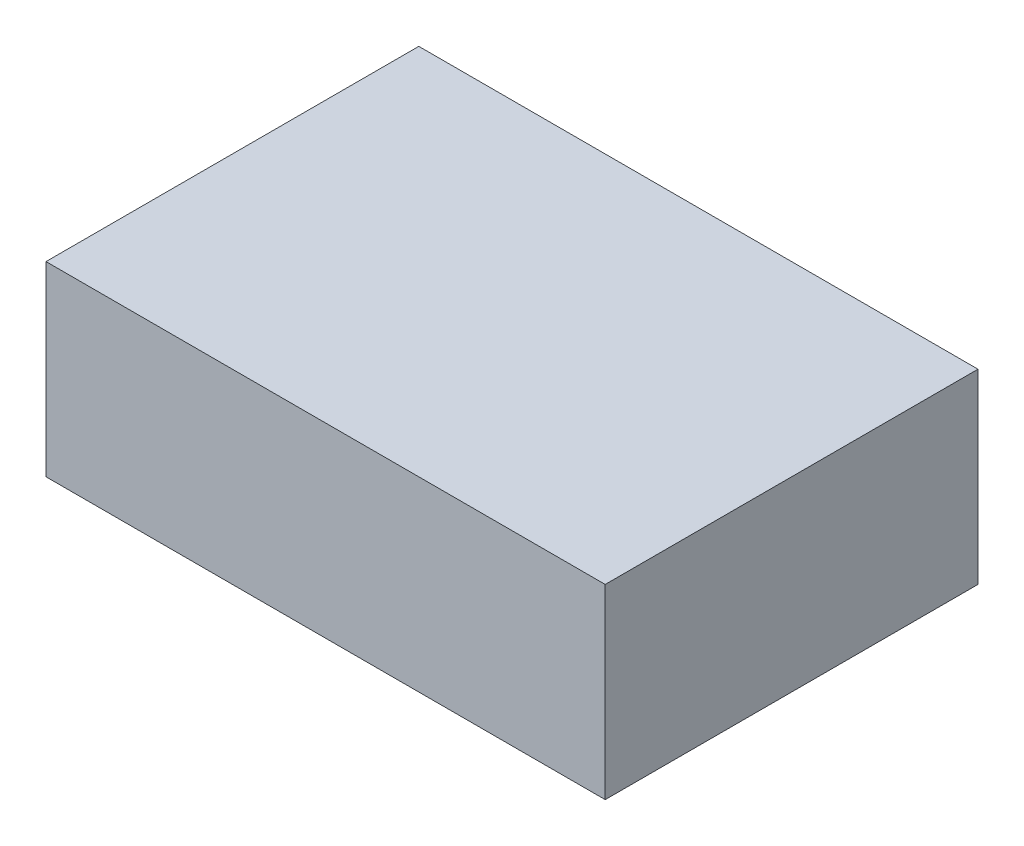
SolidWorks part; units mm, degrees
ref_plane "Front Plane" through (0, 0, 0) normal (0, 0, 1) x (1, 0, 0)
ref_plane "Top Plane" through (0, 0, 0) normal (0, 1, 0) x (1, 0, 0)
ref_plane "Right Plane" through (0, 0, 0) normal (1, 0, 0) x (0, 0, -1)
sketch "Sketch1" plane through (0, 0, 0) normal (0, 1, 0) x (1, 0, 0)
  line L1 (0, 0) -> (205.74, 0)
  line L2 (0, 0) -> (0, 137.16)
  line L3 (0, 137.16) -> (205.74, 137.16)
  line L4 (205.74, 0) -> (205.74, 137.16)
  dimension "D1" = 205.74
  dimension "D2" = 137.16
extrude "Boss-Extrude1" add sketch "Sketch1" along normal blind 68.58 contours L1 L4 L3 L2
equation "\"length\" = 8.1"
equation "\"D1@Sketch1\"=\"length\""
equation "\"width\" = 5.4"
equation "\"D2@Sketch1\"=\"width\""
equation "\"height\" = 2.7"
equation "\"D1@Boss-Extrude1\"=\"height\""
